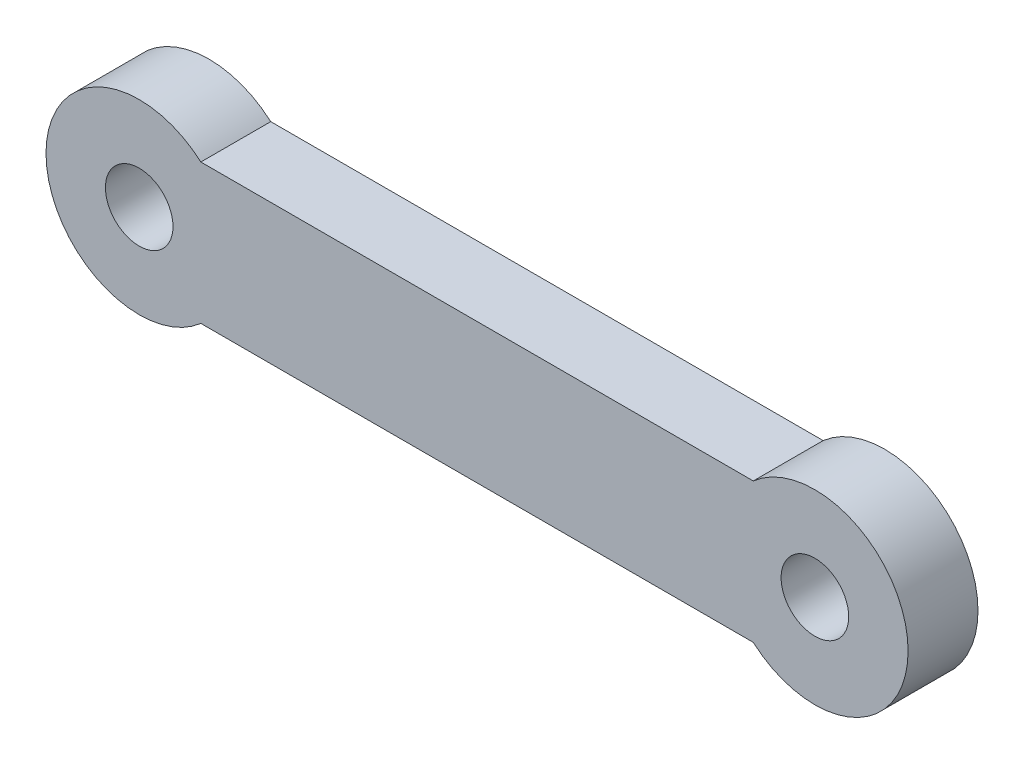
SolidWorks part; units mm, degrees
ref_plane "前视基准面" through (0, 0, 0) normal (0, 0, 1) x (1, 0, 0)
ref_plane "上视基准面" through (0, 0, 0) normal (0, 1, 0) x (1, 0, 0)
ref_plane "右视基准面" through (0, 0, 0) normal (1, 0, 0) x (0, 0, -1)
sketch "草图1" plane through (0, 0, 0) normal (0, 0, 1) x (1, 0, 0)
  line L1 (-29.3542, -3) -> (-5.6458, -3)
  line L3 (-29.3542, 3) -> (-5.6458, 3)
  circle A0 centre (-3, 0) radius 1.45
  circle A1 centre (-32, 0) radius 1.45
  arc A2 (-5.6458, -3) -> (-5.6458, 3) centre (-3, 0) ccw
  arc A3 (-29.3542, 3) -> (-29.3542, -3) centre (-32, 0) ccw
  dimension "D3" = 2.9
  dimension "D4" = 2.9
  dimension "D5" = 8
  dimension "D6" = 8
  dimension "D1" = 6
  dimension "D2" = 29
extrude "凸台-拉伸1" add sketch "草图1" along normal blind 3
